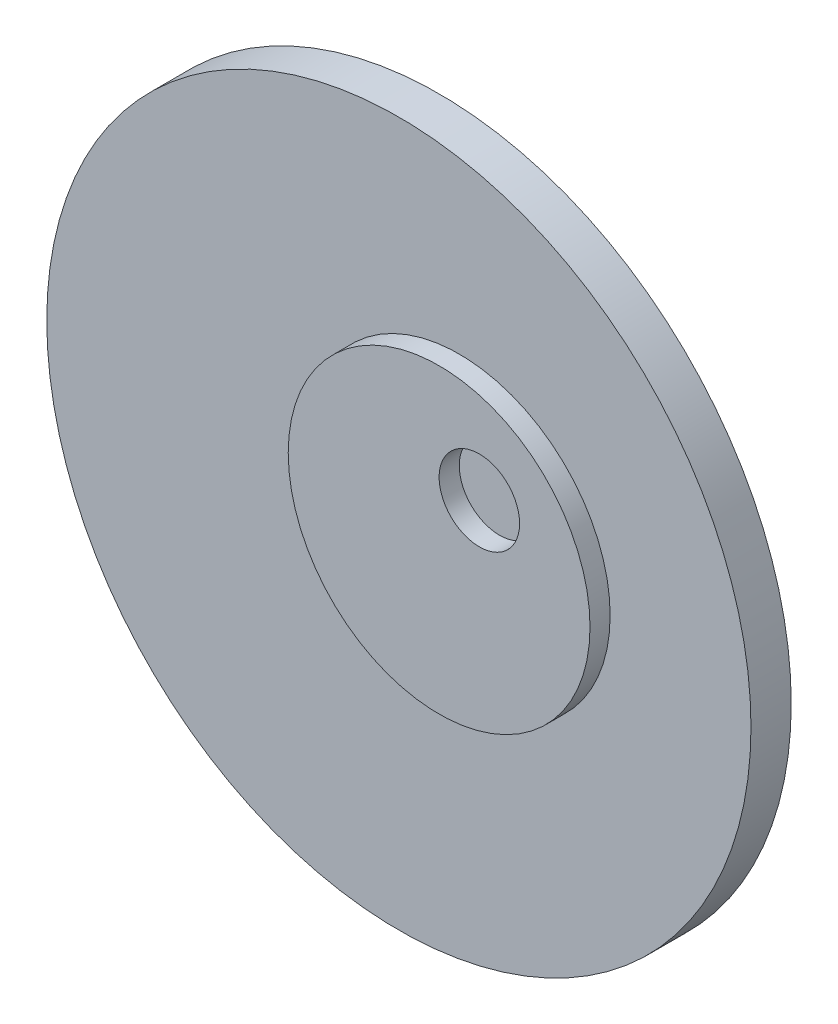
SolidWorks part; units mm, degrees
ref_plane "Front Plane" through (0, 0, 0) normal (0, 0, 1) x (1, 0, 0)
ref_plane "Top Plane" through (0, 0, 0) normal (0, 1, 0) x (1, 0, 0)
ref_plane "Right Plane" through (0, 0, 0) normal (1, 0, 0) x (0, 0, -1)
sketch "Sketch1" plane through (0, 0, 0) normal (0, 0, 1) x (1, 0, 0)
  circle A0 centre (0, 0) radius 17.5
  dimension "D1" = 35
extrude "Boss-Extrude1" add sketch "Sketch1" along normal blind 2 contours A0
sketch "Sketch2" plane through (0, 0, 2) normal (0, 0, 1) x (1, 0, 0)
  circle A0 centre (3, 1.3) radius 7.5
  circle A1 centre (5, 4) radius 2
  point P2 (5.3234, 5.4529)
  dimension "D1" = 15
  dimension "D6" = 4
  dimension "D2" = 1.3
  dimension "D3" = 3
  dimension "D4" = 4
  dimension "D5" = 5
extrude "Boss-Extrude2" add sketch "Sketch2" along normal blind 1 separate body contours A0 A1
